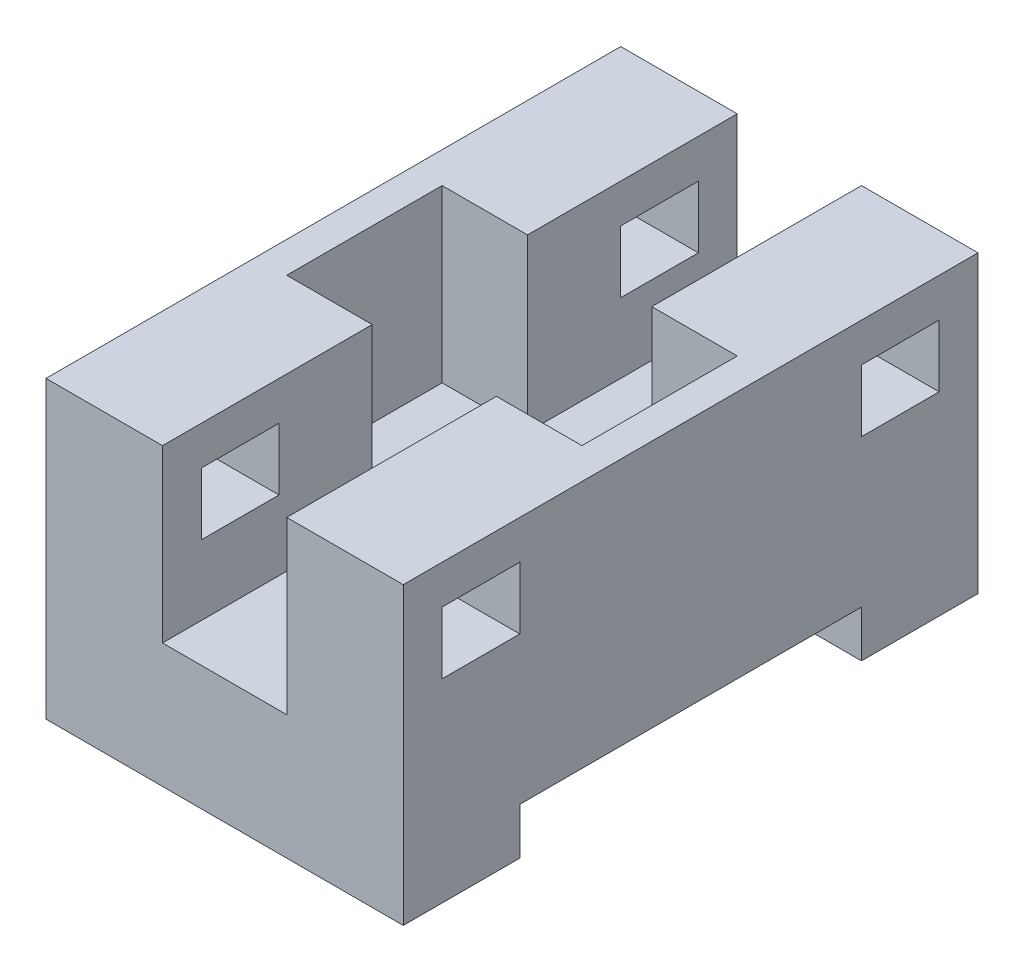
SolidWorks part; units mm, degrees
ref_plane "Alzado" through (0, 0, 0) normal (0, 0, 1) x (1, 0, 0)
ref_plane "Planta" through (0, 0, 0) normal (0, 1, 0) x (1, 0, 0)
ref_plane "Vista lateral" through (0, 0, 0) normal (1, 0, 0) x (0, 0, -1)
sketch "Croquis1" plane through (0, 0, 0) normal (1, 0, 0) x (0, 0, -1)
  line L0 (22, -19) -> (37, -19)
  line L1 (-37, 19) -> (37, 19)
  line L2 (-37, 19) -> (-37, -19)
  line L3 (-37, -19) -> (-22, -19)
  line L4 (37, 19) -> (37, -19)
  line L5 (-37, 19) -> (37, -19) construction
  line L6 (-37, -19) -> (37, 19) construction
  line L8 (-22, -19) -> (-22, -13)
  line L9 (-22, -13) -> (22, -13)
  line L10 (22, -19) -> (22, -13)
  point P0 (0, 0)
  point P10 (0, 19)
  point P11 (0, -13)
  dimension "D1" = 44
  dimension "D2" = 74
  dimension "D3" = 32
  dimension "D4" = 38
extrude "Saliente-Extruir1" add sketch "Croquis1" along normal mid plane 46
sketch "Croquis2" plane through (0, 19, 0) normal (0, 1, 0) x (1, 0, 0)
  line L0 (23, 37) -> (-23, 37) construction
  line L1 (-8, 37) -> (8, 37)
  line L2 (-8, 37) -> (-8, 10)
  line L3 (-8, -37) -> (8, -37)
  line L4 (8, 37) -> (8, 10)
  line L5 (23, -37) -> (-23, -37) construction
  line L6 (8, 10) -> (19, 10)
  line L7 (-19, 10) -> (-8, 10)
  line L8 (-19, 10) -> (-19, -10)
  line L9 (-19, -10) -> (-8, -10)
  line L10 (19, 10) -> (19, -10)
  line L11 (-8, -10) -> (-8, -37)
  line L12 (8, -10) -> (19, -10)
  line L13 (8, -10) -> (8, -37)
  point P16 (-19, 0)
  point P18 (0, 37)
  dimension "D1" = 20
  dimension "D2" = 38
  dimension "D3" = 16
extrude "Cortar-Extruir1" cut sketch "Croquis2" against normal blind 22
sketch "Croquis3" plane through (23, 0, 0) normal (1, 0, 0) x (0, 0, -1)
  line L0 (37, 19) -> (-37, 19) construction
  line L1 (22, 14) -> (32, 14)
  line L2 (22, 14) -> (22, 6)
  line L3 (22, 6) -> (32, 6)
  line L4 (32, 14) -> (32, 6)
  line L5 (37, -19) -> (37, 19) construction
  line L6 (0, 0) -> (0, 15.8564) construction
  line L7 (-22, 6) -> (-32, 6)
  line L8 (-32, 14) -> (-32, 6)
  line L9 (-22, 14) -> (-32, 14)
  line L10 (-22, 14) -> (-22, 6)
  dimension "D1" = 10
  dimension "D2" = 8
  dimension "D3" = 5
  dimension "D4" = 5
extrude "Cortar-Extruir2" cut sketch "Croquis3" against normal through all
